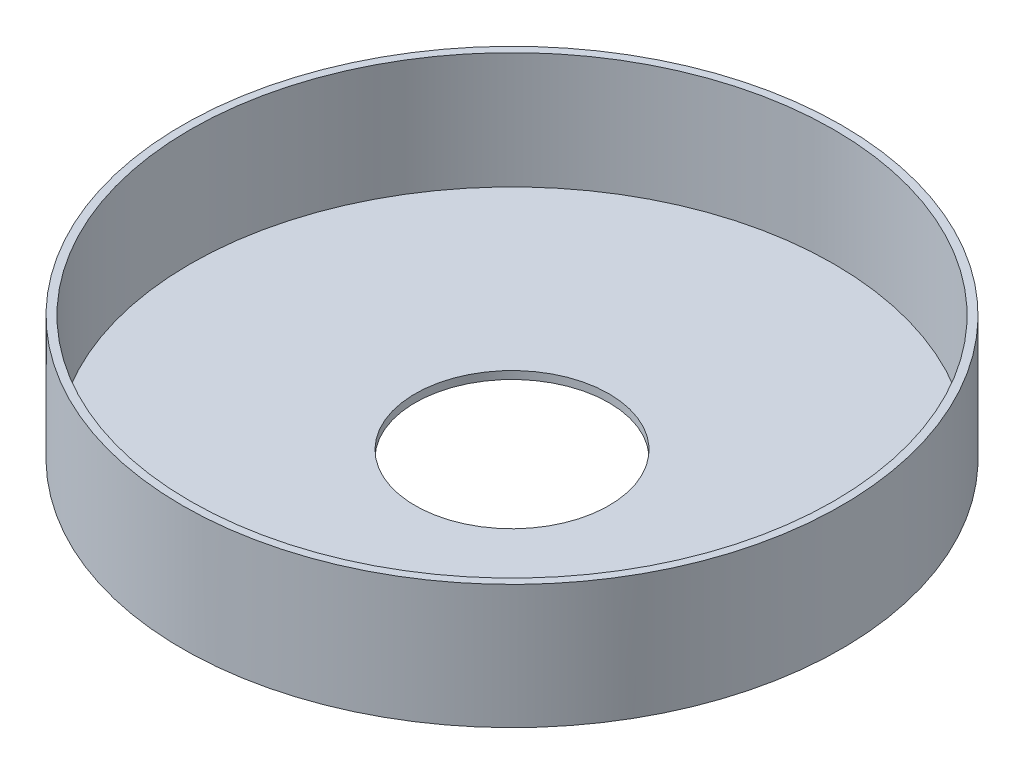
SolidWorks part; units mm, degrees
ref_plane "Front Plane" through (0, 0, 0) normal (0, 0, 1) x (1, 0, 0)
ref_plane "Top Plane" through (0, 0, 0) normal (0, 1, 0) x (1, 0, 0)
ref_plane "Right Plane" through (0, 0, 0) normal (1, 0, 0) x (0, 0, -1)
sketch "Sketch1" plane through (0, 0, 0) normal (0, 1, 0) x (1, 0, 0)
  circle A0 centre (0, 0) radius 41.5
  circle A1 centre (0, 0) radius 42.5
  dimension "D1" = 1
  dimension "D2" = 83
extrude "Boss-Extrude1" add sketch "Sketch1" along normal blind 15
sketch "Sketch2" plane through (0, 0, 0) normal (0, -1, 0) x (1, 0, 0)
  circle A0 centre (0, 0) radius 42.5
  circle A1 centre (0, 0) radius 12.5
  circle A2 centre (0, 0) radius 42.5 construction
  dimension "D1" = 25
extrude "Boss-Extrude2" add sketch "Sketch2" along normal blind 1
